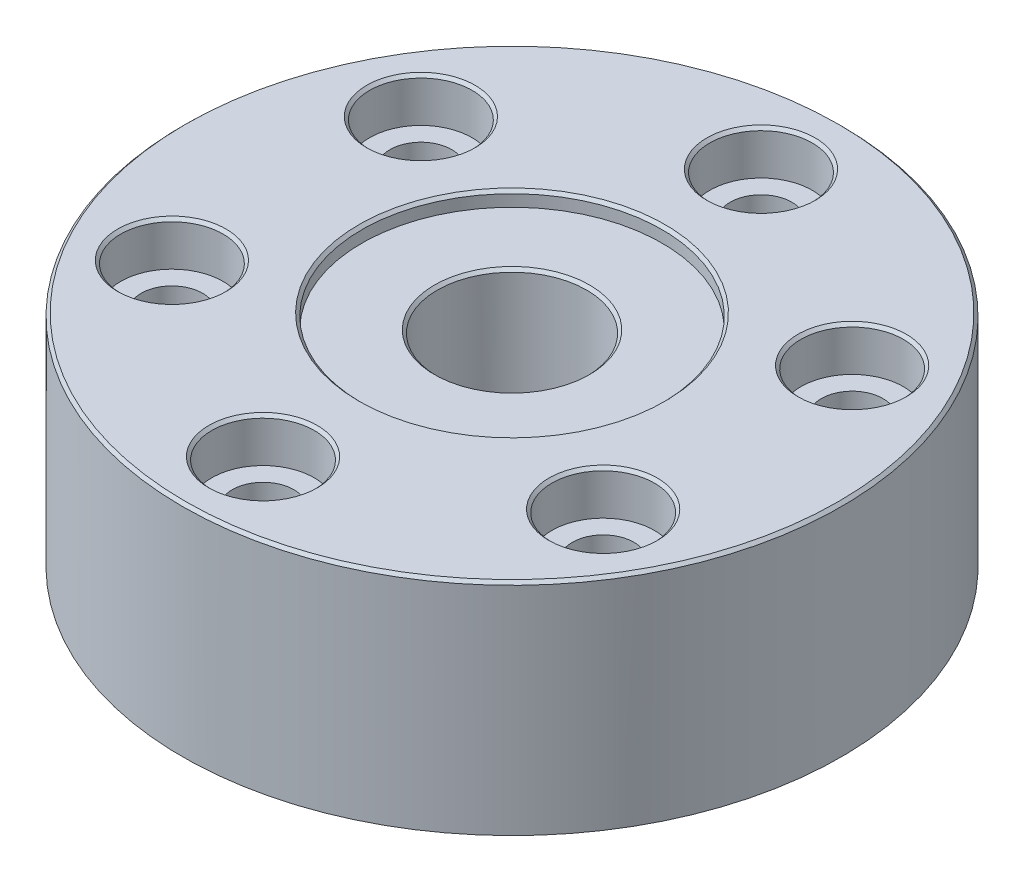
SolidWorks part; units mm, degrees
ref_plane "Front Plane" through (0, 0, 0) normal (0, 0, 1) x (1, 0, 0)
ref_plane "Top Plane" through (0, 0, 0) normal (0, 1, 0) x (1, 0, 0)
ref_plane "Right Plane" through (0, 0, 0) normal (1, 0, 0) x (0, 0, -1)
other "Configuration Table"
sketch "草图1" plane through (0, 0, 0) normal (0, 0, 1) x (1, 0, 0)
  line L0 (22.5, 15) -> (0, 15)
  line L1 (0, 15) -> (0, 0)
  line L2 (0, 0) -> (22.5, 0)
  line L3 (22.5, 0) -> (22.5, 15)
  line L4 (0, 15) -> (0, 0) construction
revolve "旋转1" add sketch "草图1" angle 360 about L4
hole_wizard "M3.5 六角头机械螺钉的柱形沉头孔1" positions "草图3" profile "草图2" counterbore size "M3.5" standard "ANSI Metric" end condition through all
sketch "草图3" plane through (0, 15, 0) normal (0, 1, 0) x (1, 0, 0)
  point P0 (14.7224, 8.5)
  point P1 (14.7224, -8.5)
  point P2 (0, -17)
  point P3 (-14.7224, -8.5)
  point P4 (-14.7224, 8.5)
  point P5 (0, 17)
sketch "草图2" plane through (14.7224, 15, -8.5) normal (1, 0, 0) x (0, 0, 1)
  line L0 (0, 0) -> (0, 15)
  line L1 (0, 15) -> (2.1, 15)
  line L3 (2.1, 15) -> (2.1, 3)
  line L4 (2.1, 3) -> (3.5, 3)
  line L5 (3.5, 3) -> (3.5, 0)
  line L7 (3.5, 0) -> (0, 0)
  line L11 (0, -6.35) -> (0, 107.95) construction
  dimension "通孔孔直径" = 4.2
  dimension "通孔孔深度" = 15
  dimension "柱形沉头孔直径" = 7
  dimension "柱形沉头孔深度" = 3
hole_wizard "孔1" positions "草图5" profile "草图4" legacy
sketch "草图5" plane through (0, 15, 0) normal (0, 1, 0) x (1, 0, 0)
  point P0 (0, 0)
sketch "草图4" plane through (0, 15, 0) normal (1, 0, 0) x (0, 0, 1)
  line L0 (0, 0) -> (0, 15)
  line L1 (0, 15) -> (5.1, 15)
  line L2 (5.1, 15) -> (5.1, 1)
  line L3 (5.1, 1) -> (10.25, 1)
  line L4 (10.25, 1) -> (10.25, 0)
  line L5 (10.25, 0) -> (0, 0)
  line L6 (0, 110) -> (0, -10) construction
  dimension "直径" = 10.2
  dimension "深度" = 15
  dimension "柱坑直径" = 20.5
  dimension "柱坑深度" = 1
chamfer "倒角1" distance 0.2 angle 45 9 edges at (0, 14, 5.1) (0, 15, 10.25) (14.7224, 15, 12) (0, 15, 20.5) (-14.7224, 15, 12) (14.7224, 15, -5) (0, 15, -13.5) (-14.7224, 15, -5) (0, 15, -22.5)
